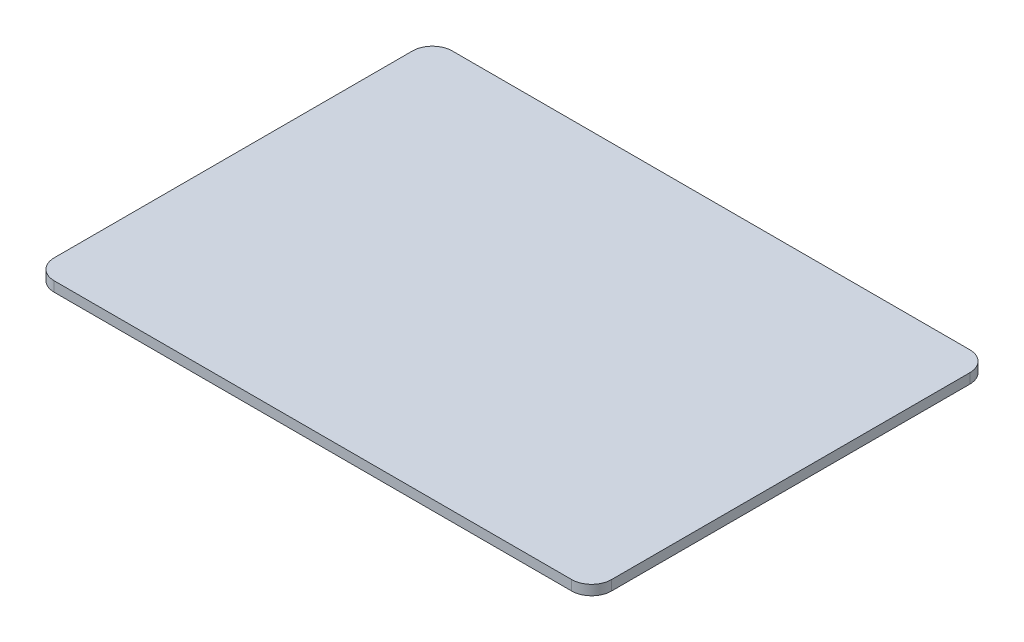
SolidWorks part; units mm, degrees
material "Pin"
ref_plane "Front" through (0, 0, 0) normal (0, 0, 1) x (1, 0, 0)
ref_plane "Top" through (0, 0, 0) normal (0, 1, 0) x (1, 0, 0)
ref_plane "Right" through (0, 0, 0) normal (1, 0, 0) x (0, 0, -1)
sketch "Esquisse1" plane through (0, 0, 0) normal (0, 1, 0) x (1, 0, 0)
  line L1 (-177.8, 127) -> (177.8, 127)
  line L2 (-177.8, 127) -> (-177.8, -127)
  line L3 (-177.8, -127) -> (177.8, -127)
  line L4 (177.8, 127) -> (177.8, -127)
  line L5 (-177.8, 127) -> (177.8, -127) construction
  line L6 (-177.8, -127) -> (177.8, 127) construction
  point P0 (0, 0)
  dimension "D1" = 355.6
  dimension "D2" = 254
extrude "Boss.-Extru.1" add sketch "Esquisse1" along normal blind 6.35
fillet "Congé1" radius 12.7 4 edges at (177.8, 3.175, 127) (-177.8, 3.175, 127) (-177.8, 3.175, -127) (177.8, 3.175, -127)
